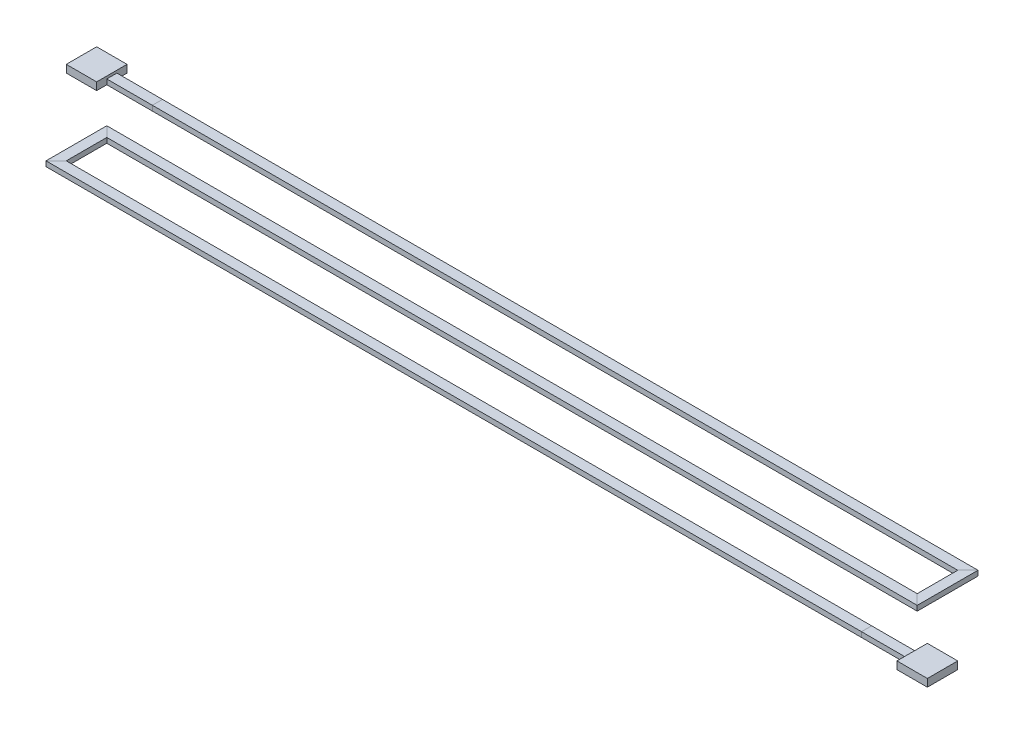
SolidWorks part; units mm, degrees
ref_plane "Front Plane" through (0, 0, 0) normal (0, 0, 1) x (1, 0, 0)
ref_plane "Top Plane" through (0, 0, 0) normal (0, 1, 0) x (1, 0, 0)
ref_plane "Right Plane" through (0, 0, 0) normal (1, 0, 0) x (0, 0, -1)
sketch "Sketch1" plane through (0, 0, 0) normal (0, 1, 0) x (1, 0, 0)
  line L0 (-40.5556, 0) -> (39.4444, 0)
  line L1 (39.4444, 0) -> (39.4444, 5)
  line L2 (39.4444, 5) -> (-40.5556, 5)
  line L3 (-40.5556, 0) -> (-40.5556, -5)
  line L4 (-40.5556, -5) -> (39.4444, -5)
  line L5 (-46.5556, 5) -> (-40.5556, 5)
  line L6 (39.4444, -5) -> (45.4444, -5)
  dimension "D1" = 5
  dimension "D2" = 80
  dimension "D3" = 5
  dimension "D4" = 6
  dimension "D5" = 6
ref_plane "Plane1" through (45.4444, 0, 0) normal (1, 0, 0) x (0, 0, -1)
sketch "Sketch2" plane through (45.4444, 0, 0) normal (1, 0, 0) x (0, 0, -1)
  line L1 (-5.5, -0.25) -> (-4.5, -0.25)
  line L2 (-5.5, -0.25) -> (-5.5, 0.25)
  line L3 (-5.5, 0.25) -> (-4.5, 0.25)
  line L4 (-4.5, -0.25) -> (-4.5, 0.25)
  line L5 (-5.5, -0.25) -> (-4.5, 0.25) construction
  line L6 (-5.5, 0.25) -> (-4.5, -0.25) construction
  point P0 (-5, 0)
  dimension "D1" = 0.5
  dimension "D2" = 1
sweep "Sweep1" add profiles "Sketch2" path "Sketch1"
sketch "Sketch3" plane through (0, -0.25, 0) normal (0, -1, 0) x (1, 0, 0)
  line L0 (-46.5556, -4.5) -> (-46.5556, -5.5) construction
  line L1 (-48.0556, -3.5) -> (-45.0556, -3.5)
  line L2 (-48.0556, -3.5) -> (-48.0556, -6.5)
  line L3 (-48.0556, -6.5) -> (-45.0556, -6.5)
  line L4 (-45.0556, -3.5) -> (-45.0556, -6.5)
  line L5 (-48.0556, -3.5) -> (-45.0556, -6.5) construction
  line L6 (-48.0556, -6.5) -> (-45.0556, -3.5) construction
  line L7 (45.4444, 5.5) -> (45.4444, 4.5) construction
  line L8 (43.9444, 6.5) -> (46.9444, 6.5)
  line L9 (43.9444, 6.5) -> (43.9444, 3.5)
  line L10 (43.9444, 3.5) -> (46.9444, 3.5)
  line L11 (46.9444, 6.5) -> (46.9444, 3.5)
  line L12 (43.9444, 6.5) -> (46.9444, 3.5) construction
  line L13 (43.9444, 3.5) -> (46.9444, 6.5) construction
  point P0 (-46.5556, -5)
  point P7 (45.4444, 5)
  dimension "D1" = 3
  dimension "D2" = 3
  dimension "D3" = 3
  dimension "D4" = 3
extrude "Boss-Extrude1" add sketch "Sketch3" against normal blind 0.75
